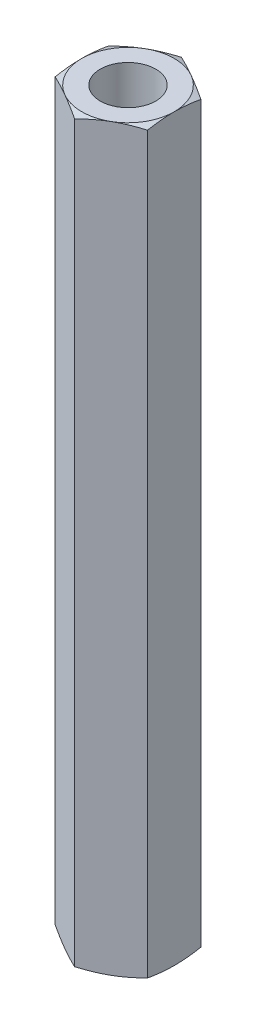
SolidWorks part; units mm, degrees
ref_plane "Front Plane" through (0, 0, 0) normal (0, 0, 1) x (1, 0, 0)
ref_plane "Top Plane" through (0, 0, 0) normal (0, 1, 0) x (1, 0, 0)
ref_plane "Right Plane" through (0, 0, 0) normal (1, 0, 0) x (0, 0, -1)
sketch "Sketch1" plane through (0, 0, 0) normal (0, 1, 0) x (1, 0, 0)
  line L1 (0, 2.8868) -> (-2.5, 1.4434)
  line L2 (-2.5, 1.4434) -> (-2.5, -1.4434)
  line L3 (-2.5, -1.4434) -> (0, -2.8868)
  line L4 (0, -2.8868) -> (2.5, -1.4434)
  line L5 (2.5, -1.4434) -> (2.5, 1.4434)
  line L6 (2.5, 1.4434) -> (0, 2.8868)
  circle A0 centre (0, 0) radius 2.5 construction
  circle A1 centre (0, 0) radius 1.5
  point P1 (2.5, 0)
  dimension "D2" = 3
  dimension "D1" = 5
extrude "Boss-Extrude1" add sketch "Sketch1" along normal blind 40
sketch "Sketch3" plane through (0, 40, 0) normal (0, 1, 0) x (1, 0, 0)
  circle A0 centre (0, 0) radius 2.5
ref_plane "Plane1" through (0, 0, 0) normal (-1, 0, 0) x (0, 0, 1)
sketch "Sketch6" plane through (0, 0, 0) normal (-1, 0, 0) x (0, 0, 1)
  line L0 (2.5, 40) -> (2.8868, 40)
  line L1 (1.4434, 40) -> (2.8868, 40) construction
  line L2 (2.5, 40) -> (-2.5, 40) construction
  line L3 (2.8868, 40) -> (2.8868, 39.8592)
  line L4 (2.8868, 40) -> (2.8868, 0) construction
  line L5 (2.8868, 39.8592) -> (2.5, 40)
  line L6 (0, 40) -> (0, 43.573) construction
  dimension "D1" = 20
  dimension "D2" = 0.3868
revolve "Cut-Revolve1" cut sketch "Sketch6" angle 360 about L6
ref_plane "Plane2" through (0, 20, 0) normal (0, 1, 0) x (1, 0, 0)
mirror "Mirror1" about plane through (0, 20, 0) normal (0, 1, 0) of "Cut-Revolve1"
